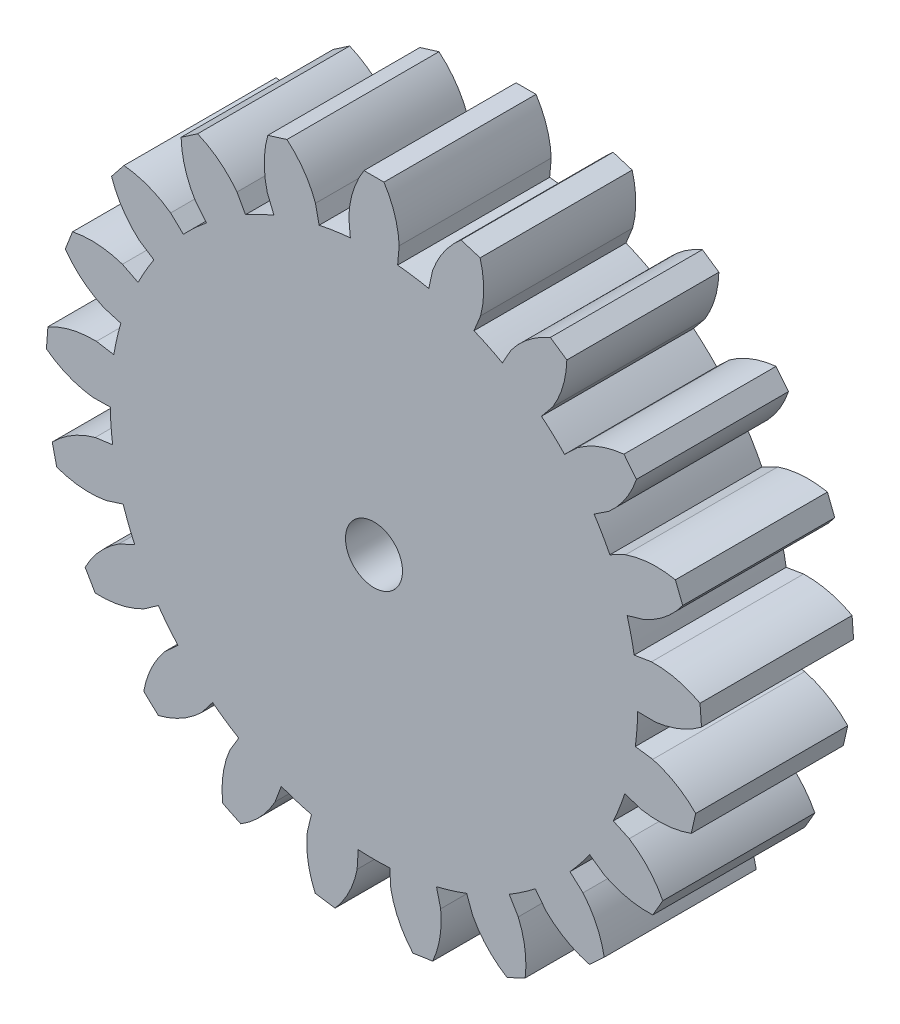
SolidWorks part; units mm, degrees
ref_plane "Front Plane" through (0, 0, 0) normal (0, 0, 1) x (1, 0, 0)
ref_plane "Top Plane" through (0, 0, 0) normal (0, 1, 0) x (1, 0, 0)
ref_plane "Right Plane" through (0, 0, 0) normal (1, 0, 0) x (0, 0, -1)
sketch "Sketch2" plane through (0, 0, 0) normal (0, 0, 1) x (1, 0, 0)
  circle A0 centre (0, 0) radius 13.875
  dimension "D1" = 27.75
extrude "Boss-Extrude1" add sketch "Sketch2" along normal blind 8
sketch "Sketch3" plane through (0, 0, 0) normal (0, 0, 1) x (1, 0, 0)
  line L0 (0, 0) -> (0, 20) construction
  line L1 (0, 0) -> (1.3259, 14.7405)
  line L3 (0, 0) -> (0.5256, 17.242) construction
  line L4 (0, 0) -> (-1.3259, 14.7405)
  line L5 (-0.5256, 17.242) -> (0.5256, 17.242)
  arc A2 (1.3259, 14.7405) -> (0.5256, 17.242) centre (-3.6976, 14.512) ccw
  arc A3 (-1.3259, 14.7405) -> (-0.5256, 17.242) centre (3.6976, 14.512) cw
extrude "Boss-Extrude2" add sketch "Sketch3" along normal blind 8 contours L5 A2 L1 L4 A3
pattern_circular "CirPattern2" count 21 over 360 about axis through (0, 0, 0) along (0, 0, 1) of "Boss-Extrude2"
sketch "Sketch5" plane through (0, 0, 8) normal (0, 0, 1) x (1, 0, 0)
  circle A0 centre (0, 0) radius 1.5
  dimension "D1" = 3
extrude "Middle Hole" cut sketch "Sketch5" against normal blind 8
